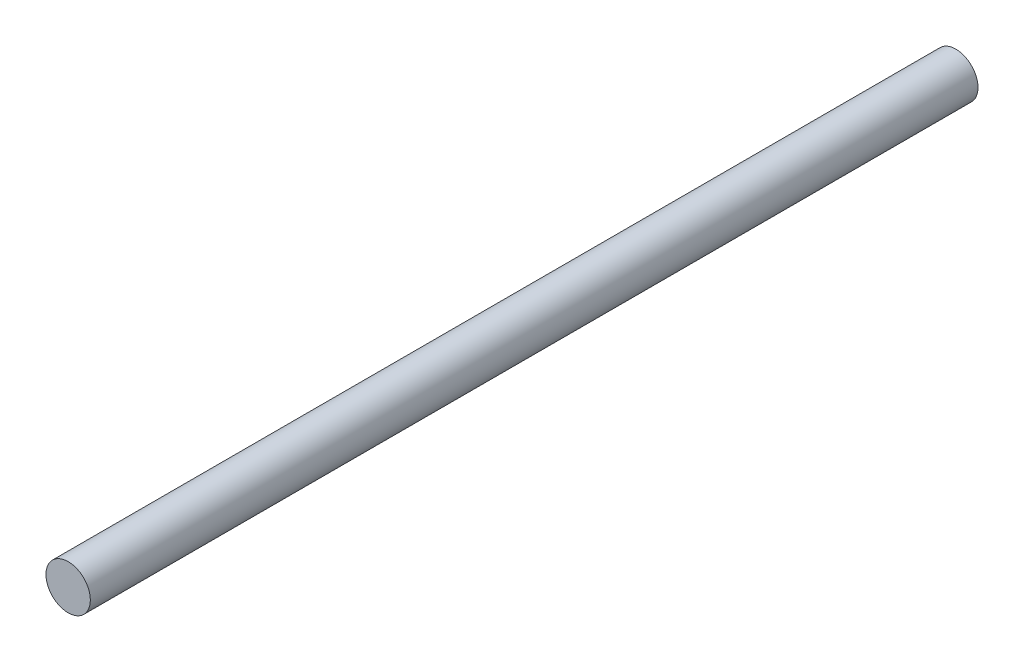
SolidWorks part; units mm, degrees
material "Thornel Mat VMA"
ref_plane "Front Plane" through (0, 0, 0) normal (0, 0, 1) x (1, 0, 0)
ref_plane "Top Plane" through (0, 0, 0) normal (0, 1, 0) x (1, 0, 0)
ref_plane "Right Plane" through (0, 0, 0) normal (1, 0, 0) x (0, 0, -1)
sketch "Sketch1" plane through (0, 0, 0) normal (0, 0, 1) x (1, 0, 0)
  circle A0 centre (0, 0) radius 2.5
extrude "Boss-Extrude1" add sketch "Sketch1" along normal blind 100
